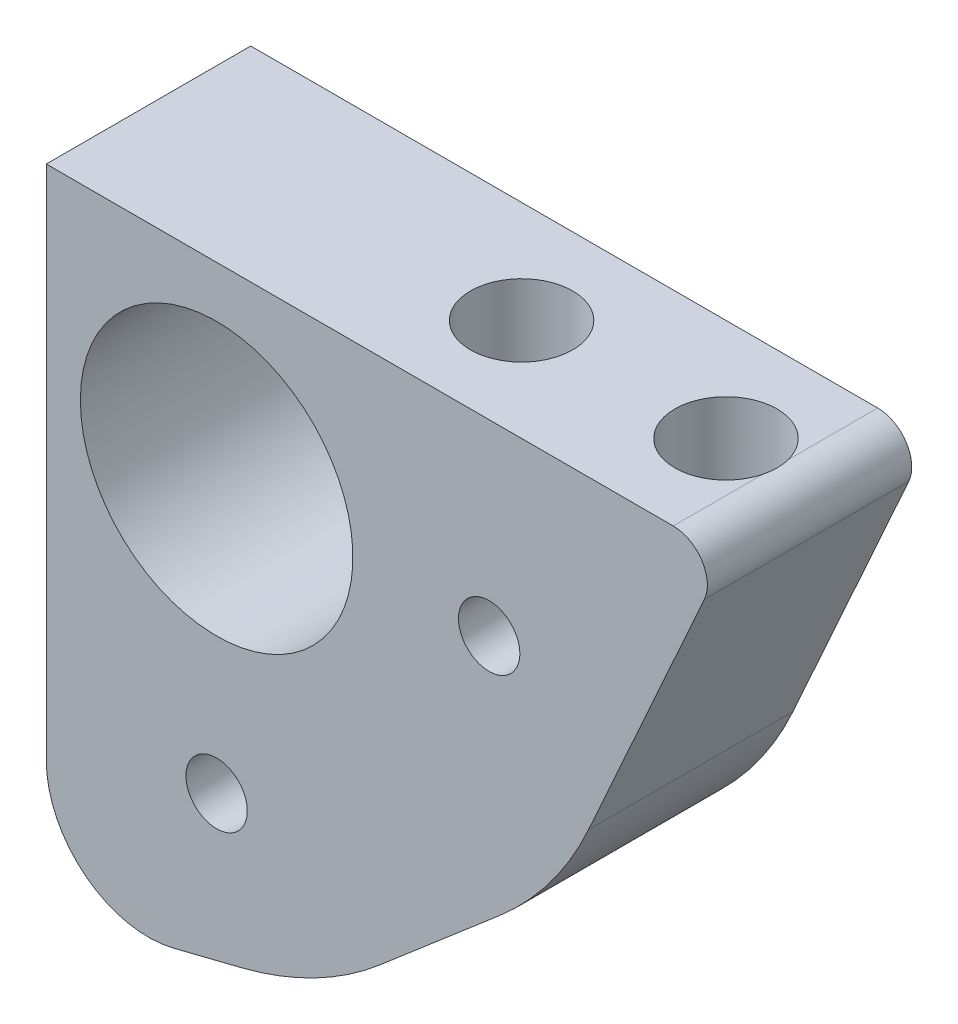
SolidWorks part; units mm, degrees
ref_plane "Plan de face" through (0, 0, 0) normal (0, 0, 1) x (1, 0, 0)
ref_plane "Plan de dessus" through (0, 0, 0) normal (0, 1, 0) x (1, 0, 0)
ref_plane "Plan de droite" through (0, 0, 0) normal (1, 0, 0) x (0, 0, -1)
sketch "Esquisse2" plane through (0, 0, 0) normal (0, 0, 1) x (1, 0, 0)
  line L0 (-7.3174, -8.6655) -> (0.6826, -6.6655)
  line L1 (7.6826, -0.6655) -> (12.634, 10.3345)
  line L3 (7.6826, 10.3345) -> (-7.3174, 10.3345)
  line L4 (-7.3174, 10.3345) -> (-7.3174, -8.6655)
  line L5 (7.6826, -0.6655) -> (0.6826, -6.6655)
  line L6 (12.634, 10.3345) -> (7.6826, 10.3345)
  point P0 (0, 0)
  dimension "D6" = 8
  dimension "D8" = 6
  dimension "D1" = 19
  dimension "D4" = 8
extrude "Boss.-Extru.1" add sketch "Esquisse2" along normal blind 6 contours L4 L0 L5 L1 L6 L3
sketch "Esquisse5" plane through (0, 0, 0) normal (0, 0, -1) x (-1, 0, 0)
  line L1 (7.3174, 10.3345) -> (7.3174, -8.6655) construction
  line L2 (2.3174, 12.8345) -> (2.3174, 4.8345) construction
  line L3 (2.3174, 4.8345) -> (2.3174, -3.1655) construction
  line L4 (-10.1583, 4.8345) -> (7.3174, 4.8345) construction
  line L12 (7.3174, 10.3345) -> (7.3174, -8.6655) construction
  line L13 (-7.6826, -0.6655) -> (-12.634, 10.3345) construction
  circle A0 centre (2.3174, 4.8345) radius 4
  circle A2 centre (-5.6826, 4.8345) radius 0.9
  circle A3 centre (2.3174, -3.1655) radius 0.9
  dimension "D5" = 8
  dimension "D6" = 1.8
  dimension "D8" = 1.8
  dimension "D1" = 8
  dimension "D2" = 8
  dimension "D3" = 8
  dimension "D4" = 5
extrude "Enlèv. mat.-Extru.1" cut sketch "Esquisse5" against normal through all
fillet "Congé3" radius 10 2 edges at (0.6826, -6.6655, 3) (7.6826, -0.6655, 3)
fillet "Congé4" radius 3 1 edges at (-7.3174, -8.6655, 3)
sketch "Esquisse10" plane through (0, 10.3345, 0) normal (0, 1, 0) x (1, 0, 0)
  line L0 (12.634, -6) -> (12.634, 0) construction
  line L1 (12.634, 0) -> (-7.3174, 0) construction
  circle A0 centre (3.634, -3) radius 1.5
  circle A1 centre (9.634, -3) radius 1.5
  point P4 (12.634, -3)
  dimension "D1" = 3
  dimension "D2" = 3
  dimension "D3" = 3
  dimension "D4" = 3
  dimension "D5" = 3
  dimension "D6" = 6
fillet "Congé5" radius 1 1 edges at (12.634, 10.3345, 3)
extrude "Enlèv. mat.-Extru.7" cut sketch "Esquisse10" against normal blind 3
